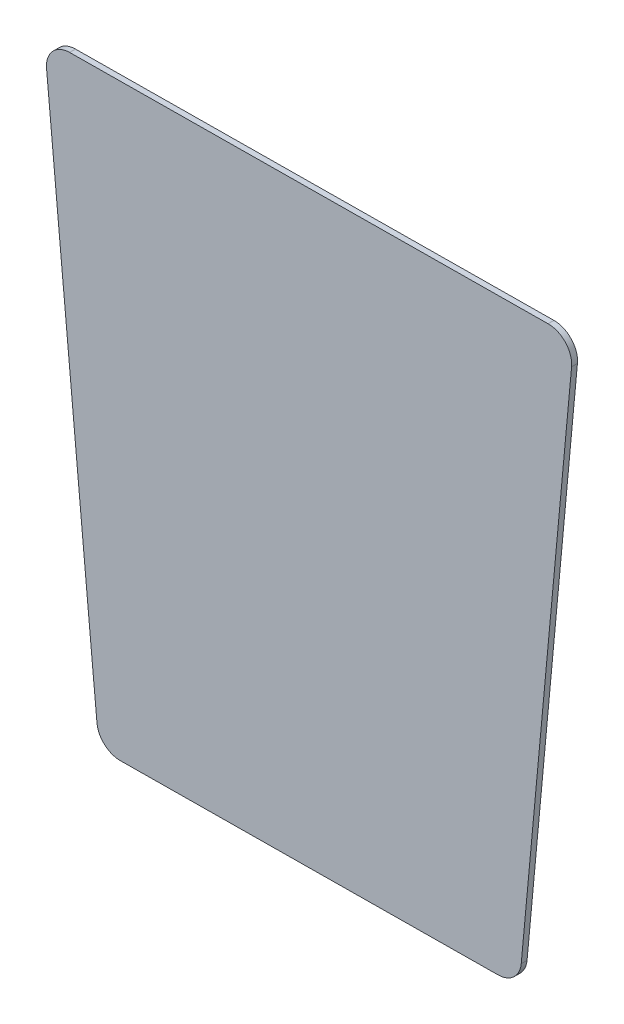
SolidWorks part; units mm, degrees
material "Acrylic (Medium-high impact)"
ref_plane "Front Plane" through (0, 0, 0) normal (0, 0, 1) x (1, 0, 0)
ref_plane "Top Plane" through (0, 0, 0) normal (0, 1, 0) x (1, 0, 0)
ref_plane "Right Plane" through (0, 0, 0) normal (1, 0, 0) x (0, 0, -1)
sketch "Sketch1" plane through (0, 0, 1353.8753) normal (0, 0, 1) x (1, 0, 0)
  line L0 (-114.199, 112.2485) -> (-143.9351, 431.734) construction
  line L1 (114.199, 114.2679) -> (-114.199, 112.2485) construction
  line L2 (143.9351, 434.2967) -> (114.199, 114.2679) construction
  line L3 (-143.9351, 431.734) -> (143.9351, 434.2967) construction
  line L4 (-114.199, 112.2485) -> (-143.9351, 431.734)
  line L5 (114.199, 114.2679) -> (-114.199, 112.2485)
  line L6 (143.9351, 434.2967) -> (114.199, 114.2679)
  line L7 (-143.9351, 431.734) -> (143.9351, 434.2967)
extrude "Boss-Extrude1" add sketch "Sketch1" along normal up to vertex (3.175 mm away) from vertex at 0
fillet "Fillet1" radius 12.7 4 edges at (-114.199, 112.2485, 1355.4628) (143.9351, 434.2967, 1355.4628) (114.199, 114.2679, 1355.4628) (-143.9351, 431.734, 1355.4628)
